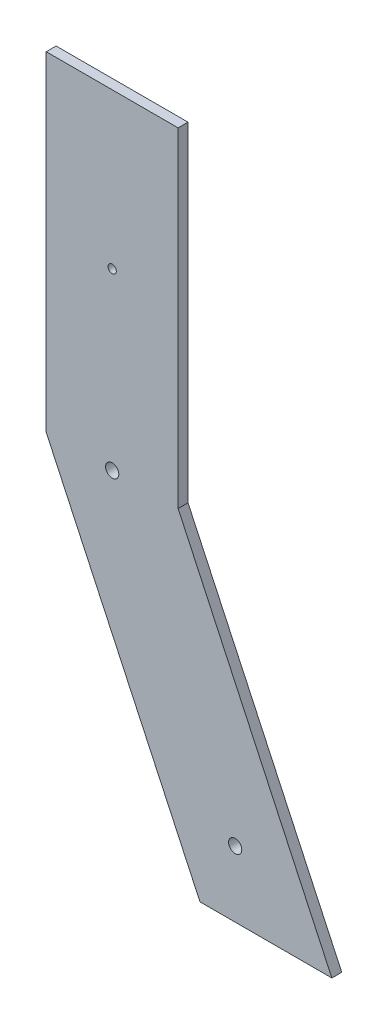
SolidWorks part; units mm, degrees
ref_plane "Front Plane" through (0, 0, 0) normal (0, 0, 1) x (1, 0, 0)
ref_plane "Top Plane" through (0, 0, 0) normal (0, 1, 0) x (1, 0, 0)
ref_plane "Right Plane" through (0, 0, 0) normal (1, 0, 0) x (0, 0, -1)
sketch "Croquis1" plane through (0, 0, 0) normal (0, 0, 1) x (1, 0, 0)
  line L0 (0, 0) -> (-40, 0)
  line L1 (-86.6308, 100) -> (-46.6308, 100) construction
  line L2 (-86.6308, 100) -> (-40, 0)
  line L3 (-46.6308, 100) -> (0, 0)
  line L4 (-86.6308, 100) -> (-86.6308, 200)
  line L5 (-86.6308, 200) -> (-46.6308, 200)
  line L6 (-46.6308, 200) -> (-46.6308, 100)
  line L7 (-29.3262, 20) -> (-20, 0) construction
  line L8 (-66.6308, 152.96) -> (-66.6308, 200) construction
  line L9 (-66.6308, 152.96) -> (-66.6308, 100) construction
  circle A0 centre (-29.3262, 20) radius 2
  circle A1 centre (-66.6308, 152.96) radius 1.25
  circle A2 centre (-66.6308, 100) radius 2
  dimension "D6" = 4
  dimension "D8" = 2.5
  dimension "D9" = 4
  dimension "D1" = 100
  dimension "D2" = 40
  dimension "D3" = 65
  dimension "D4" = 100
  dimension "D5" = 20
  dimension "D7" = 47.04
extrude "Saliente-Extruir1" add sketch "Croquis1" along normal blind 3
